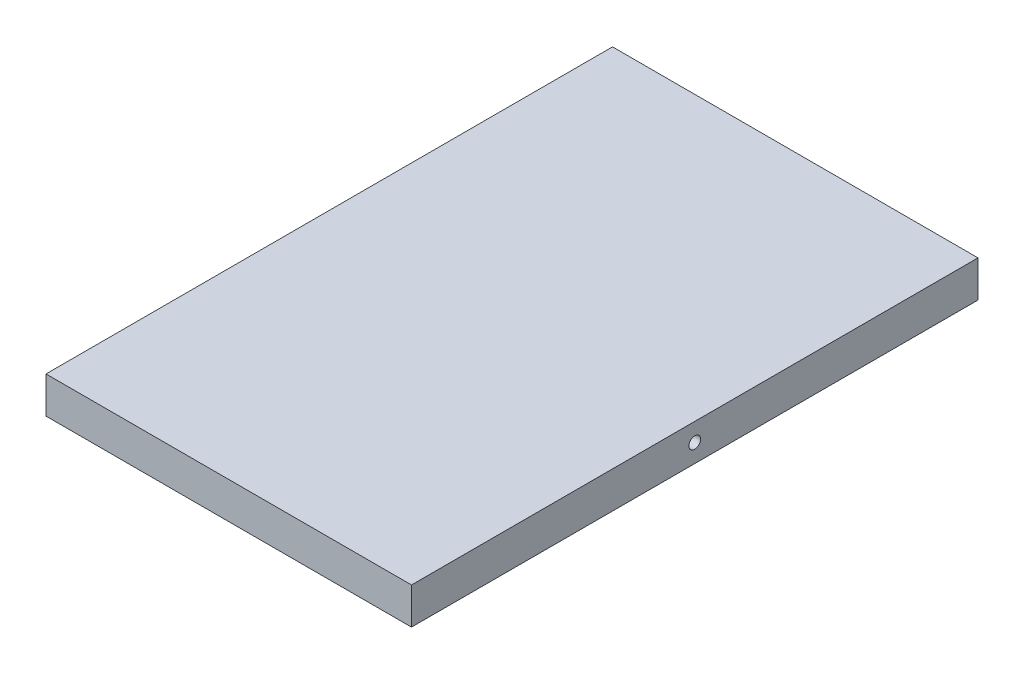
SolidWorks part; units mm, degrees
ref_plane "Front Plane" through (0, 0, 0) normal (0, 0, 1) x (1, 0, 0)
ref_plane "Top Plane" through (0, 0, 0) normal (0, 1, 0) x (1, 0, 0)
ref_plane "Right Plane" through (0, 0, 0) normal (1, 0, 0) x (0, 0, -1)
sketch "Sketch1" plane through (0, 0, 0) normal (0, 1, 0) x (1, 0, 0)
  line L1 (0, 0) -> (500, 0)
  line L2 (0, 0) -> (0, 775)
  line L3 (0, 775) -> (500, 775)
  line L4 (500, 0) -> (500, 775)
  dimension "D1" = 775
  dimension "D2" = 500
extrude "Boss-Extrude1" add sketch "Sketch1" along normal blind 50
sketch "Sketch2" plane through (500, 0, 0) normal (1, 0, 0) x (0, 0, -1)
  line L0 (0, 50) -> (0, 0) construction
  line L1 (0, 0) -> (775, 0) construction
  circle A0 centre (387.5, 25) radius 8
  dimension "D1" = 16
  dimension "D3" = 25
  dimension "D2" = 387.5
extrude "Cut-Extrude1" cut sketch "Sketch2" against normal blind 45
sketch "Sketch3" plane through (0, 0, 0) normal (-1, 0, 0) x (0, 0, 1)
  line L0 (-775, 50) -> (-775, 0) construction
  line L1 (-775, 50) -> (0, 50) construction
  circle A0 centre (-387.5, 25) radius 8
  dimension "D1" = 16
  dimension "D2" = 387.5
  dimension "D3" = 25
extrude "Cut-Extrude2" cut sketch "Sketch3" against normal blind 45
sketch "Sketch4" plane through (0, 0, 0) normal (0, -1, 0) x (-1, 0, 0)
  line L0 (0, 775) -> (0, 0) construction
  line L1 (0, 0) -> (-500, 0) construction
  circle A0 centre (-250, 100) radius 66.5483
  dimension "D1" = 250
  dimension "D2" = 100
extrude "Boss-Extrude2" add sketch "Sketch4" along normal blind 60.75
fillet "Fillet1" radius 60 1 edges at (250, -60.75, -166.5483)
